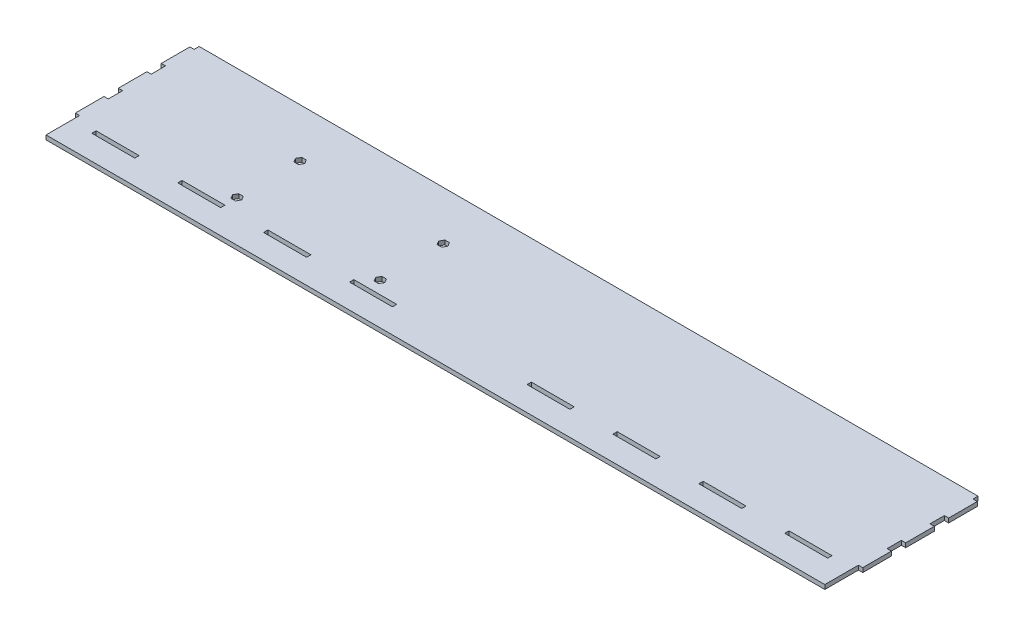
SolidWorks part; units mm, degrees
ref_plane "Front Plane" through (0, 0, 0) normal (0, 0, 1) x (1, 0, 0)
ref_plane "Top Plane" through (0, 0, 0) normal (0, 1, 0) x (1, 0, 0)
ref_plane "Right Plane" through (0, 0, 0) normal (1, 0, 0) x (0, 0, -1)
sketch "Sketch1" plane through (0, 0, 0) normal (0, 1, 0) x (1, 0, 0)
  line L0 (0, 53.5) -> (0, 0) construction
  line L1 (-272, 53.5) -> (272, 53.5)
  line L2 (-272, 53.5) -> (-272, -53.5)
  line L3 (-272, -53.5) -> (272, -53.5)
  line L4 (272, 53.5) -> (272, -53.5)
  line L5 (0, 0) -> (272, 0) construction
  dimension "D1" = 544
  dimension "D2" = 107
extrude "Boss-Extrude1" add sketch "Sketch1" along normal blind 3
sketch "Sketch2" plane through (0, 3, 0) normal (0, 1, 0) x (1, 0, 0)
  line L0 (0, 0) -> (0, -53.5) construction
  line L1 (47, -36.5) -> (77, -36.5)
  line L2 (47, -36.5) -> (47, -33.5)
  line L3 (47, -33.5) -> (77, -33.5)
  line L4 (77, -36.5) -> (77, -33.5)
  line L5 (-272, -53.5) -> (272, -53.5) construction
  line L6 (107, -36.5) -> (107, -33.5)
  line L7 (107, -36.5) -> (137, -36.5)
  line L8 (137, -36.5) -> (137, -33.5)
  line L9 (107, -33.5) -> (137, -33.5)
  line L10 (167, -36.5) -> (167, -33.5)
  line L11 (167, -36.5) -> (197, -36.5)
  line L12 (197, -36.5) -> (197, -33.5)
  line L13 (167, -33.5) -> (197, -33.5)
  line L14 (227, -36.5) -> (227, -33.5)
  line L15 (227, -36.5) -> (257, -36.5)
  line L16 (257, -36.5) -> (257, -33.5)
  line L17 (227, -33.5) -> (257, -33.5)
  line L18 (-47, -33.5) -> (-77, -33.5)
  line L19 (-77, -36.5) -> (-77, -33.5)
  line L20 (-47, -36.5) -> (-47, -33.5)
  line L21 (-47, -36.5) -> (-77, -36.5)
  line L22 (-107, -36.5) -> (-137, -36.5)
  line L23 (-137, -36.5) -> (-137, -33.5)
  line L24 (-107, -33.5) -> (-137, -33.5)
  line L25 (-107, -36.5) -> (-107, -33.5)
  line L26 (-167, -36.5) -> (-197, -36.5)
  line L27 (-197, -36.5) -> (-197, -33.5)
  line L28 (-167, -33.5) -> (-197, -33.5)
  line L29 (-167, -36.5) -> (-167, -33.5)
  line L30 (-227, -36.5) -> (-257, -36.5)
  line L31 (-257, -36.5) -> (-257, -33.5)
  line L32 (-227, -33.5) -> (-257, -33.5)
  line L33 (-227, -36.5) -> (-227, -33.5)
  dimension "D1" = 3
  dimension "D2" = 30
  dimension "D3" = 47
  dimension "D4" = 17
  dimension "D5" = 4
extrude "Cut-Extrude1" cut sketch "Sketch2" against normal blind 3
sketch "Sketch3" plane through (0, 3, 0) normal (0, 1, 0) x (1, 0, 0)
  line L0 (-117.5, 23.5) -> (-117.5, -2.5) construction
  line L1 (-176, 33.5) -> (-272, 33.5)
  line L2 (-176, 33.5) -> (-176, -28.5)
  line L3 (-176, -28.5) -> (-272, -28.5)
  line L4 (-272, 33.5) -> (-272, -28.5)
  line L5 (-171, -28.5) -> (-64, -28.5)
  line L6 (-171, -28.5) -> (-171, 23.5)
  line L7 (-171, 23.5) -> (-64, 23.5)
  line L8 (-64, -28.5) -> (-64, 23.5)
  line L9 (-117.5, -2.5) -> (-64, -2.5) construction
  line L10 (-117.5, 19.5) -> (-117.5, -2.5) construction
  line L11 (-167.5, 19.5) -> (-67.5, 19.5) construction
  line L12 (-167.5, 19.5) -> (-167.5, -24.5) construction
  line L13 (-167.5, -24.5) -> (-67.5, -24.5) construction
  line L14 (-67.5, 19.5) -> (-67.5, -24.5) construction
  line L15 (-117.5, -2.5) -> (-67.5, -2.5) construction
  line L16 (-272, 53.5) -> (-272, -53.5) construction
  line L17 (-227, -33.5) -> (-257, -33.5) construction
  dimension "D1" = 62
  dimension "D2" = 96
  dimension "D3" = 107
  dimension "D4" = 52
  dimension "D5" = 5
  dimension "D6" = 100
  dimension "D7" = 44
  dimension "D8" = 5
sketch "Sketch4" plane through (0, 3, 0) normal (0, 1, 0) x (1, 0, 0)
  line L1 (-164.3246, 19.5) -> (-165.9123, 22.25)
  line L2 (-165.9123, 22.25) -> (-169.0877, 22.25)
  line L3 (-169.0877, 22.25) -> (-170.6754, 19.5)
  line L4 (-170.6754, 19.5) -> (-169.0877, 16.75)
  line L5 (-169.0877, 16.75) -> (-165.9123, 16.75)
  line L6 (-165.9123, 16.75) -> (-164.3246, 19.5)
  line L7 (-164.3246, -24.5) -> (-165.9123, -21.75)
  line L8 (-165.9123, -21.75) -> (-169.0877, -21.75)
  line L9 (-169.0877, -21.75) -> (-170.6754, -24.5)
  line L10 (-170.6754, -24.5) -> (-169.0877, -27.25)
  line L11 (-169.0877, -27.25) -> (-165.9123, -27.25)
  line L12 (-165.9123, -27.25) -> (-164.3246, -24.5)
  line L13 (-70.6754, 19.5) -> (-69.0877, 16.75)
  line L14 (-69.0877, 16.75) -> (-65.9123, 16.75)
  line L15 (-65.9123, 16.75) -> (-64.3246, 19.5)
  line L16 (-64.3246, 19.5) -> (-65.9123, 22.25)
  line L17 (-65.9123, 22.25) -> (-69.0877, 22.25)
  line L18 (-69.0877, 22.25) -> (-70.6754, 19.5)
  line L19 (-70.6754, -24.5) -> (-69.0877, -27.25)
  line L20 (-69.0877, -27.25) -> (-65.9123, -27.25)
  line L21 (-65.9123, -27.25) -> (-64.3246, -24.5)
  line L22 (-64.3246, -24.5) -> (-65.9123, -21.75)
  line L23 (-65.9123, -21.75) -> (-69.0877, -21.75)
  line L24 (-69.0877, -21.75) -> (-70.6754, -24.5)
  circle A0 centre (-167.5, 19.5) radius 2.75 construction
  circle A1 centre (-167.5, -24.5) radius 2.75 construction
  circle A2 centre (-67.5, 19.5) radius 2.75 construction
  circle A3 centre (-67.5, -24.5) radius 2.75 construction
  dimension "D1" = 5.5
extrude "Cut-Extrude2" cut sketch "Sketch4" against normal blind 3
sketch "Sketch5" plane through (0, 0, 0) normal (0, 1, 0) x (1, 0, 0)
  line L5 (-272, 0) -> (-275, 0) construction
  line L6 (-272, 53.5) -> (-272, -53.5) construction
  line L7 (-272, 20) -> (-272, 0)
  line L8 (-272, -10) -> (-275, -10)
  line L9 (-272, -10) -> (-272, -30)
  line L10 (-272, -30) -> (-275, -30)
  line L11 (-275, -10) -> (-275, -30)
  line L12 (-272, 20) -> (-275, 20)
  line L13 (-275, 20) -> (-275, 0)
  line L14 (-272, 0) -> (-275, 0)
  line L15 (-272, 50) -> (-272, 30)
  line L16 (-272, 50) -> (-275, 50)
  line L17 (-275, 50) -> (-275, 30)
  line L18 (-272, 30) -> (-275, 30)
  dimension "D1" = 3
  dimension "D2" = 10
  dimension "D3" = 20
  dimension "D4" = 3
extrude "Boss-Extrude2" add sketch "Sketch5" along normal blind 3
mirror "Mirror1" about plane through (0, 0, 0) normal (1, 0, 0) of "Boss-Extrude2"
